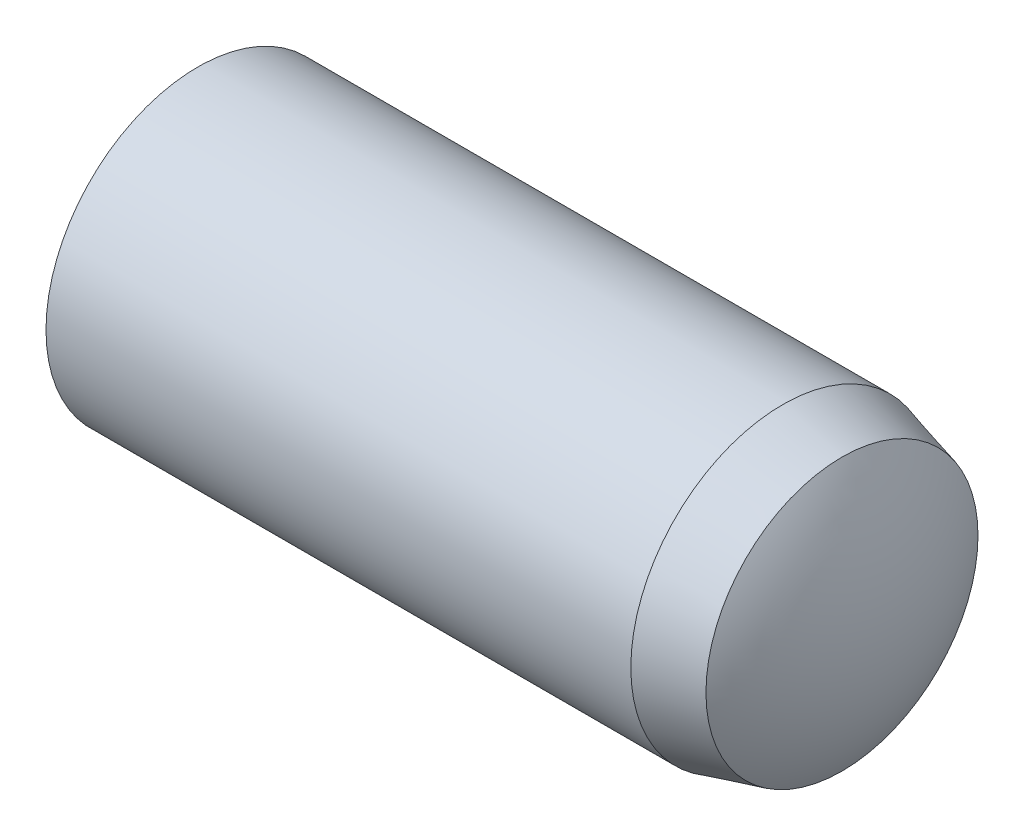
SolidWorks part; units mm, degrees
ref_plane "Front Plane" through (0, 0, 0) normal (0, 0, 1) x (1, 0, 0)
ref_plane "Top Plane" through (0, 0, 0) normal (0, 1, 0) x (1, 0, 0)
ref_plane "Right Plane" through (0, 0, 0) normal (1, 0, 0) x (0, 0, -1)
sketch "Sketch1" plane through (0, 0, 0) normal (0, 0, 1) x (1, 0, 0)
  line L0 (-6, 0) -> (6, 0) construction
  line L1 (6, 2.5) -> (6, -2.5) construction
  line L2 (-6, 2.5) -> (-6, -2.5) construction
  line L3 (4.375, 2.5) -> (4.375, -2.5) construction
  line L4 (-5.25, 2.5) -> (-5.25, -2.5) construction
  line L5 (-6, 0) -> (-5.25, 0) construction
  line L6 (6, 0) -> (4.375, 0) construction
  line L7 (5.35, 2.5) -> (5.35, -2.5) construction
  dimension "Dia" = 5
  dimension "Length" = 12
  dimension "D1" = 1.625
  dimension "D2" = 0.75
  dimension "D3" = 0.975
sketch "Sketch2" plane through (0, 0, 0) normal (1, 0, 0) x (0, 0, -1)
  circle A0 centre (0, 0) radius 2.5
extrude "Extrude1" add sketch "Sketch2" against normal up to vertex (6 mm away) and the other way up to vertex (6 mm away) up to point (-6, 0, 0) other way up to point (6, 0, 0)
sketch "Sketch5" plane through (0, 0, 0) normal (0, 0, 1) x (1, 0, 0)
  line L0 (4.375, 2.5) -> (4.375, 3)
  line L1 (4.375, 3) -> (6.5, 3)
  line L2 (6.5, 3) -> (6.5, 0)
  line L3 (6, 0) -> (6.5, 0)
  line L5 (-5.25, 2.5) -> (-5.25, 3)
  line L6 (-5.25, 3) -> (-6.5, 3)
  line L7 (-6.5, 3) -> (-6.5, 0)
  line L8 (4.375, 2.5) -> (5.35, 2.2387)
  line L10 (-6, 0) -> (-6.5, 0)
  line L11 (-6, 2.5) -> (-6, -2.5) construction
  line L13 (4.375, 2.5) -> (4.375, -2.5) construction
  line L15 (-6, 0) -> (6, 0) construction
  line L16 (5.35, 2.5) -> (5.35, -2.5) construction
  line L17 (6, 2.5) -> (6, -2.5) construction
  arc A0 (5.35, 2.2387) -> (6, 0) centre (1.8196, 0) cw
  arc A1 (-5.25, 2.5) -> (-6, 0) centre (-1.4583, 0) ccw
  dimension "D1" = 15
  dimension "D2" = 0.5
revolve "Cut-Revolve1" cut sketch "Sketch5" angle 360 about L0
equation "\"D1@Sketch1\" = \"Dia@Sketch1\"*.325"
equation "\"D2@Sketch1\" = \"Dia@Sketch1\"*.15"
equation "\"D3@Sketch1\" = \"D1@Sketch1\"*.6"
